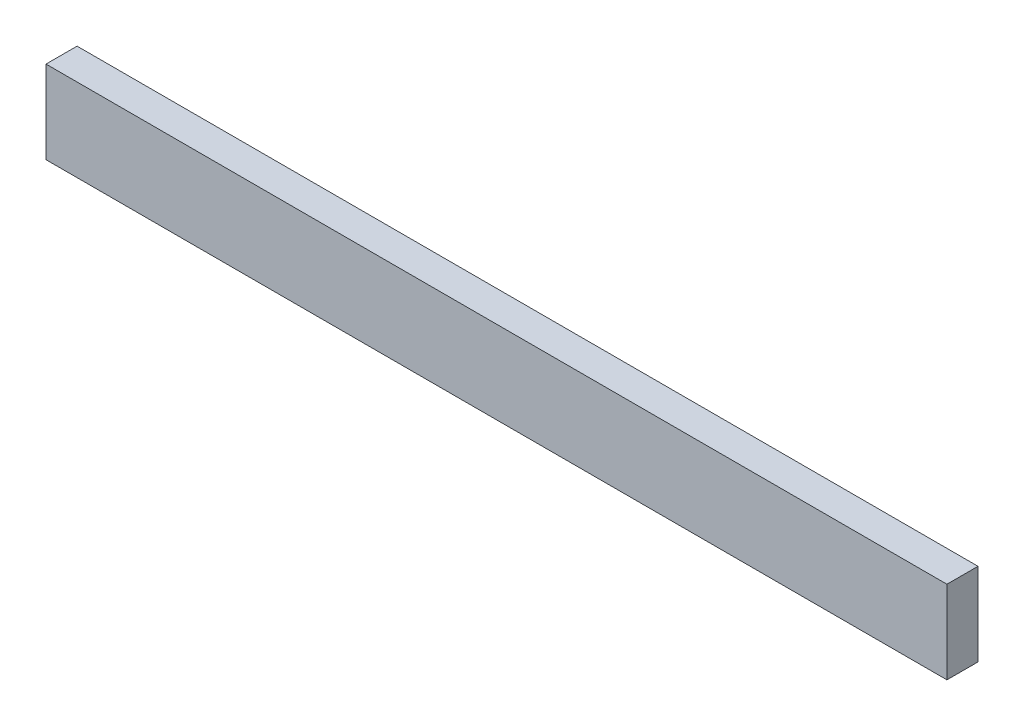
SolidWorks part; units mm, degrees
ref_plane "Front Plane" through (0, 0, 0) normal (0, 0, 1) x (1, 0, 0)
ref_plane "Top Plane" through (0, 0, 0) normal (0, 1, 0) x (1, 0, 0)
ref_plane "Right Plane" through (0, 0, 0) normal (1, 0, 0) x (0, 0, -1)
sketch "Sketch1" plane through (0, 0, 0) normal (0, 0, 1) x (1, 0, 0)
  line L1 (0, 0) -> (552.45, 0)
  line L2 (0, 0) -> (0, 50.8)
  line L3 (0, 50.8) -> (552.45, 50.8)
  line L4 (552.45, 0) -> (552.45, 50.8)
  line L5 (0, 0) -> (552.45, 50.8) construction
  line L6 (0, 50.8) -> (552.45, 0) construction
  point P4 (276.225, 25.4)
  dimension "D1" = 50.8
  dimension "D2" = 552.45
extrude "Boss-Extrude1" add sketch "Sketch1" along normal blind 19.05
